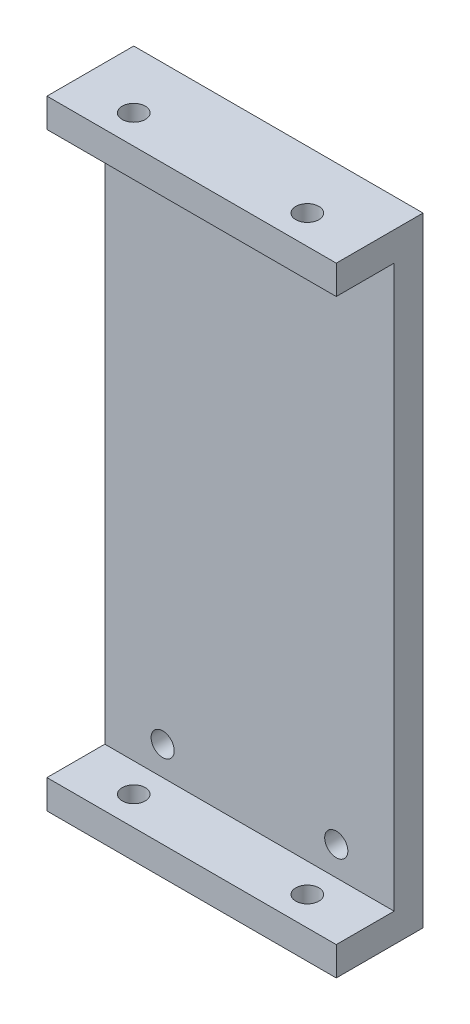
SolidWorks part; units mm, degrees
ref_plane "Front Plane" through (0, 0, 0) normal (0, 0, 1) x (1, 0, 0)
ref_plane "Top Plane" through (0, 0, 0) normal (0, 1, 0) x (1, 0, 0)
ref_plane "Right Plane" through (0, 0, 0) normal (1, 0, 0) x (0, 0, -1)
sketch "Sketch1" plane through (0, 0, 0) normal (0, 1, 0) x (1, 0, 0)
  line L1 (-25, -7.5) -> (25, -7.5)
  line L2 (-25, -7.5) -> (-25, 7.5)
  line L3 (-25, 7.5) -> (25, 7.5)
  line L4 (25, -7.5) -> (25, 7.5)
  line L5 (-25, -7.5) -> (25, 7.5) construction
  line L6 (-25, 7.5) -> (25, -7.5) construction
  point P0 (0, 0)
  dimension "D1" = 50
  dimension "D2" = 15
extrude "Boss-Extrude1" add sketch "Sketch1" against normal blind 5
sketch "Sketch2" plane through (0, 0, 0) normal (0, 1, 0) x (1, 0, 0)
  line L0 (25, -7.5) -> (25, 7.5) construction
  line L1 (-25, 7.5) -> (25, 7.5)
  line L2 (-25, 7.5) -> (-25, 2.5)
  line L3 (-25, 2.5) -> (25, 2.5)
  line L4 (25, 7.5) -> (25, 2.5)
  dimension "D1" = 5
extrude "Boss-Extrude2" add sketch "Sketch2" along normal blind 97
sketch "Sketch3" plane through (0, 97, 0) normal (0, 1, 0) x (1, 0, 0)
  line L0 (-25, -7.5) -> (25, -7.5) construction
  line L1 (-25, 7.5) -> (25, 7.5)
  line L2 (-25, 7.5) -> (-25, -7.5)
  line L3 (-25, -7.5) -> (25, -7.5)
  line L4 (25, 7.5) -> (25, -7.5)
  point P7 (25, -7.5)
extrude "Boss-Extrude3" add sketch "Sketch3" along normal blind 5
hole_wizard "Ø4.0mm Dowel Hole1" positions "3DSketch1" profile "Sketch4" hole size "Ø4.0" standard "ANSI Metric"
sketch3d "3DSketch1"
  line L0 (-25, 97, -2.5) -> (25, 97, -2.5) construction
  line L1 (-25, 0, -2.5) -> (25, 0, -2.5) construction
  line L2 (15, 97, -2.5) -> (-15, 97, -2.5) construction
  line L4 (15, 0, -2.5) -> (-15, 0, -2.5) construction
  line L5 (25, 97, 7.5) -> (25, 97, -2.5) construction
  line L6 (25, 0, 7.5) -> (25, 0, -2.5) construction
  line L7 (15, 97, 2.5) -> (15, 97, -2.5) construction
  line L8 (15, 97, -2.5) -> (15, 92, -2.5) construction
  line L10 (15, 0, 2.5) -> (15, 0, -2.5) construction
  line L11 (15, 0, -2.5) -> (15, 5, -2.5) construction
  point P0 (-15, 0, 2.5)
  point P2 (15, 0, 2.5)
  point P4 (-15, 5, -2.5)
  point P6 (15, 5, -2.5)
  point P8 (-15, 92, -2.5)
  point P10 (15, 92, -2.5)
  point P12 (15, 97, 2.5)
  point P14 (-15, 97, 2.5)
  point P17 (-15, 97, -2.5)
  point P21 (15, 97, -2.5)
  point P23 (15, 0, -2.5)
  point P27 (-15, 0, -2.5)
  point P46 (0, 0, -2.5)
  point P53 (25, 97, 2.5)
  point P57 (25, 0, 2.5)
  dimension "D1" = 30
sketch "Sketch4" plane through (-15, 0, 2.5) normal (1, 0, 0) x (0, 0, 1)
  line L0 (0, 0) -> (0, 5)
  line L1 (0, 5) -> (2, 5)
  line L2 (2, 5) -> (2, 0)
  line L5 (2, 0) -> (0, 0)
  line L11 (0, -6.35) -> (0, 107.95) construction
  dimension "Thru Hole Dia." = 4
  dimension "Thru Hole Depth" = 5
